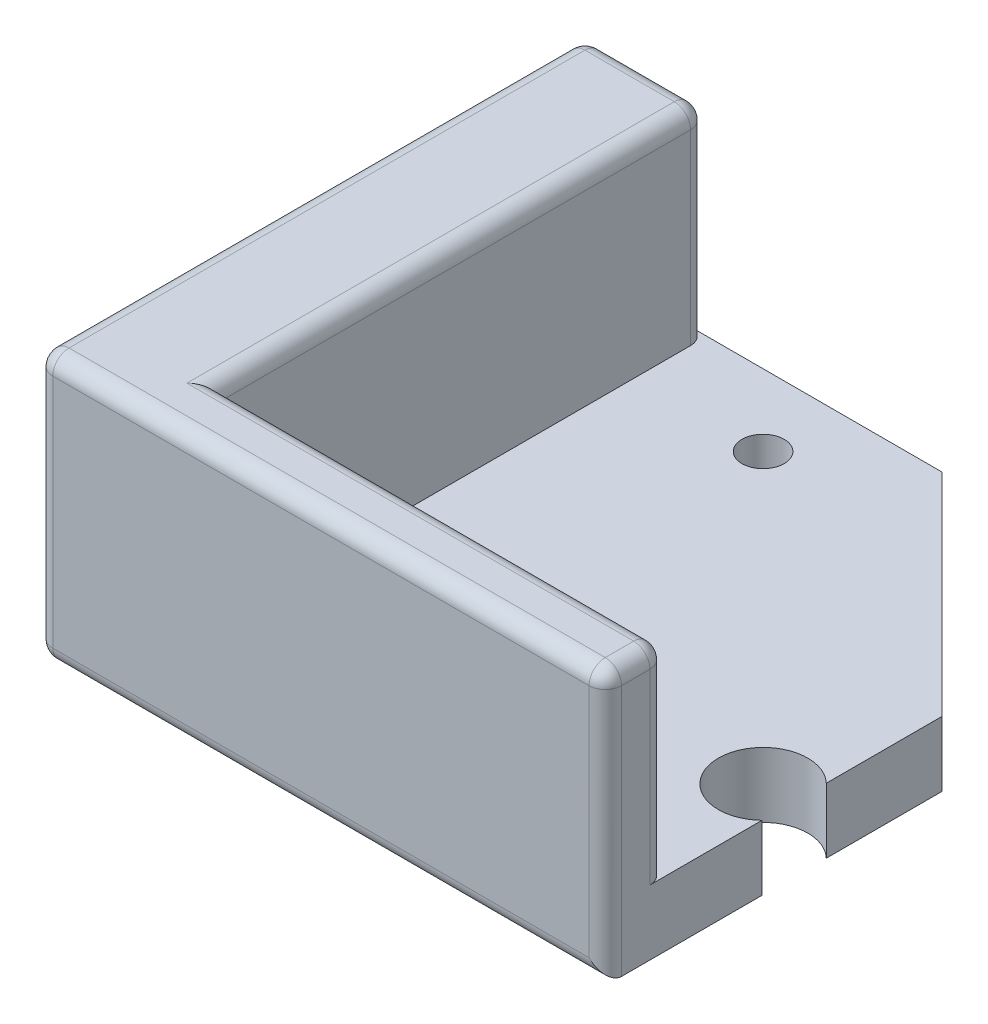
SolidWorks part; units mm, degrees
ref_plane "Front Plane" through (0, 0, 0) normal (0, 0, 1) x (1, 0, 0)
ref_plane "Top Plane" through (0, 0, 0) normal (0, 1, 0) x (1, 0, 0)
ref_plane "Right Plane" through (0, 0, 0) normal (1, 0, 0) x (0, 0, -1)
sketch "Sketch1" plane through (0, 0, 0) normal (0, 1, 0) x (1, 0, 0)
  line L0 (0, 0) -> (38.1, 0)
  line L1 (38.1, 0) -> (38.1, 2.3813)
  line L2 (38.1, 2.3813) -> (2.3813, 2.3812)
  line L3 (2.3813, 2.3812) -> (2.3812, 38.1)
  line L4 (2.3812, 38.1) -> (0, 38.1)
  line L5 (0, 38.1) -> (0, 0)
  dimension "D1" = 38.1
  dimension "D2" = 38.1
  dimension "D3" = 2.3813
  dimension "D4" = 2.3813
extrude "Boss-Extrude1" add sketch "Sketch1" along normal blind 2.54
sketch "Sketch2" plane through (0, 2.54, 0) normal (0, 1, 0) x (1, 0, 0)
  line L0 (2.3813, 2.3812) -> (2.3812, 38.1) construction
  line L1 (0, 38.1) -> (-9.525, 38.1)
  line L2 (0, 38.1) -> (0, 0)
  line L3 (0, 0) -> (-9.525, 0)
  line L4 (-9.525, 38.1) -> (-9.525, 0)
  line L5 (38.1, 0) -> (-9.525, 0)
  line L6 (38.1, 0) -> (38.1, -9.525)
  line L7 (38.1, -9.525) -> (-9.525, -9.525)
  line L8 (-9.525, 0) -> (-9.525, -9.525)
  line L9 (38.1, 2.3813) -> (2.3813, 2.3812) construction
  line M11 (0, 38.1) -> (0, 0)
  line M12 (0, 0) -> (38.1, 0)
  dimension "D1" = 11.9062
  dimension "D2" = 11.9062
extrude "Boss-Extrude2" add sketch "Sketch2" against normal blind 15.875 contours L1 L4 L3 M11 | L3 L8 L7 L6 M12
sketch "Sketch3" plane through (0, -13.335, 0) normal (0, -1, 0) x (-1, 0, 0)
  line L0 (-38.1, 0) -> (-38.1, -9.525) construction
  line L1 (9.525, -9.525) -> (-38.1, -9.525)
  line L2 (9.525, -9.525) -> (9.525, 38.1)
  line L3 (9.525, 38.1) -> (-18.3731, 38.1)
  line L4 (-38.1, -9.525) -> (-38.1, 18.3731)
  line L5 (0, 38.1) -> (9.525, 38.1) construction
  line L7 (-38.1, 18.3731) -> (-18.3731, 38.1)
  dimension "D1" = 45
extrude "Boss-Extrude3" add sketch "Sketch3" along normal blind 5.08
hole_wizard "M3 Clearance Hole1" positions "Sketch5" profile "Sketch6" hole size "M3" standard "ANSI Metric"
sketch "Sketch5" plane through (0, -18.415, 0) normal (0, -1, 0) x (-1, 0, 0)
  point P0 (-10, 32.5)
  point P2 (-32.5, 10)
  dimension "D1" = 32.5
  dimension "D2" = 32.5
  dimension "D3" = 10
  dimension "D4" = 10
sketch "Sketch6" plane through (10, -18.415, -32.5) normal (1, 0, 0) x (0, 0, -1)
  line L0 (0, 0) -> (0, 13.6914)
  line L1 (0, 13.6914) -> (1.65, 12.7)
  line L2 (1.65, 12.7) -> (1.65, 0)
  line L5 (1.65, 0) -> (0, 0)
  line L10 (0, 13.6914) -> (-1.65, 12.7) construction
  line L11 (0, -6.35) -> (0, 107.95) construction
  dimension "Hole Dia." = 3.3
  dimension "Hole Depth" = 12.7
  dimension "Drill Angle" = 118
sketch "Sketch7" plane through (0, 2.54, 0) normal (0, 1, 0) x (1, 0, 0)
  line L0 (2.3812, 0) -> (38.1, 0)
  line L1 (2.3812, 38.1) -> (0, 38.1)
  line L2 (2.3812, 38.1) -> (2.3812, 0)
  line L3 (2.3812, 0) -> (0, 0)
  line L4 (0, 38.1) -> (0, 0)
  line L9 (38.1, 0) -> (38.1, 2.3813)
  line L10 (38.1, 2.3813) -> (2.3813, 2.3812)
  line M1 (2.3812, 38.1) -> (-9.525, 38.1)
  line M4 (38.1, -9.525) -> (38.1, 2.3813)
  line M5 (38.1, 2.3813) -> (2.3813, 2.3812)
  line M6 (2.3813, 2.3812) -> (2.3812, 38.1)
extrude "Cut-Extrude1" cut sketch "Sketch7" against normal blind 2.54 contours L2 L0 M5 M4 | L4 L3 L2 M1 M6
fillet "Fillet1" radius 1.27 13 edges at (38.1, 2.54, 4.7625) (0, -5.3975, -38.1) (-9.525, -7.9375, -38.1) (38.1, -5.3975, 0) (14.2875, 2.54, 9.525) (38.1, -7.9375, 9.525) (-9.525, -7.9375, 9.525) (-9.525, 2.54, -14.2875) (-9.525, -18.415, -14.2875) (14.2875, -18.415, 9.525) (-4.7625, 2.54, -38.1) (0, 2.54, -19.05) (19.05, 2.54, 0)
sketch "Sketch8" plane through (0, -13.335, 0) normal (0, 1, 0) x (1, 0, 0)
  circle A0 centre (32.5, 10) radius 3.4925
  dimension "D1" = 6.985
extrude "Cut-Extrude2" cut sketch "Sketch8" against normal blind 10.16
sketch "Sketch9" plane through (0, 2.54, 0) normal (0, 1, 0) x (1, 0, 0)
  line L0 (36.83, -9.525) -> (-8.255, -9.525) construction
  line L1 (38.1, -9.525) -> (-20.8344, -9.525)
  line L2 (38.1, -9.525) -> (38.1, -4.7625)
  line L3 (38.1, -4.7625) -> (-20.8344, -4.7625)
  line L4 (-20.8344, -9.525) -> (-20.8344, -4.7625)
  line L6 (38.1, -1.27) -> (38.1, -8.255) construction
  line L13 (38.1, -4.7625) -> (34.925, -4.7625)
  line L14 (38.1, -4.7625) -> (38.1, 24.3984)
  line L15 (38.1, 24.3984) -> (34.925, 24.3984)
  line L16 (34.925, -4.7625) -> (34.925, 24.3984)
  point P9 (38.1, -4.7625)
  line M5 (36.83, -1.27) -> (-1.27, -1.27)
  line M8 (-8.255, 36.83) -> (-8.255, -8.255)
  line M9 (-8.255, -8.255) -> (36.83, -8.255)
  line M10 (36.83, -8.255) -> (36.83, -1.27)
  dimension "D1" = 29.1609
  dimension "D2" = 3.175
extrude "Cut-Extrude3" cut sketch "Sketch9" against normal through all contours L16 L3 L14 L15 M5 M10 | L3 M10 M8 M9 | L4 L1 L2 L3 M10 M9 M8 | L16 L3 M10 M5
fillet "Fillet2" radius 1.27 9 edges at (34.925, -6.0325, 0) (34.925, 2.168, 0.372) (-9.153, -18.043, 4.7625) (-9.153, 2.168, 4.7625) (34.925, 2.54, 3.0163) (34.925, -7.9375, 4.7625) (13.335, -18.415, 4.7625) (-9.525, -7.9375, 4.7625) (13.335, 2.54, 4.7625)
